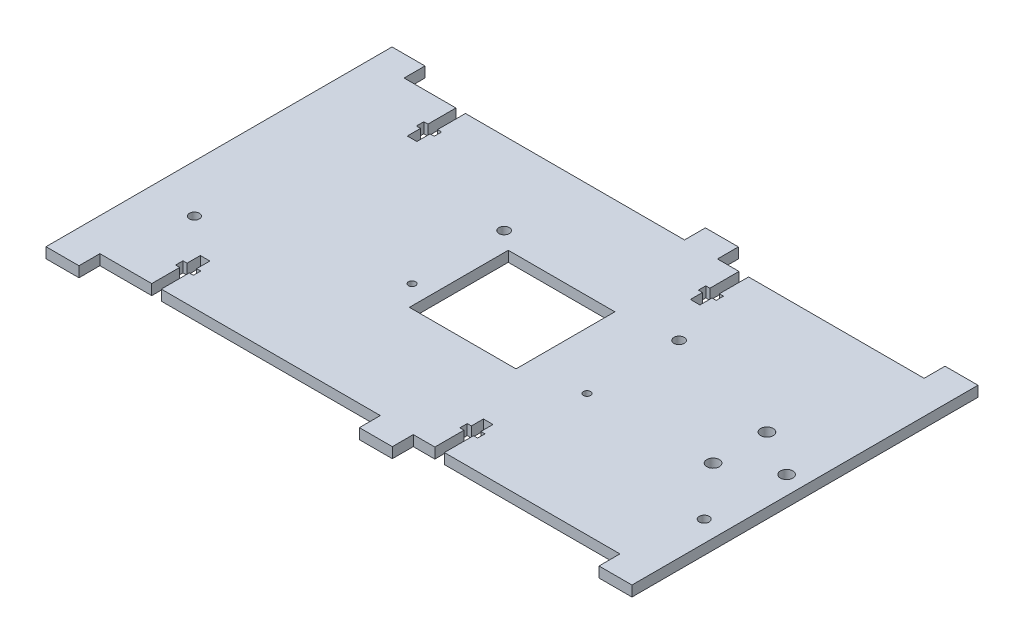
SolidWorks part; units mm, degrees
ref_plane "Front Plane" through (0, 0, 0) normal (0, 0, 1) x (1, 0, 0)
ref_plane "Top Plane" through (0, 0, 0) normal (0, 1, 0) x (1, 0, 0)
ref_plane "Right Plane" through (0, 0, 0) normal (1, 0, 0) x (0, 0, -1)
sketch "Sketch1" plane through (0, 0, 0) normal (0, 1, 0) x (1, 0, 0)
  line L0 (-67.1586, 70.4843) -> (-67.1586, 74.4928)
  line L1 (-92.8881, 91.5843) -> (-82.8881, 91.5843)
  line L2 (-92.8881, 91.5843) -> (-92.8881, -13.4157)
  line L3 (84.9141, 91.5843) -> (84.9141, -13.4157)
  line L5 (-64.2586, 85.2343) -> (2.2019, 85.2343)
  line L6 (-67.1586, 85.2343) -> (-67.1586, 76.7428)
  line L7 (-67.1586, 70.4843) -> (-64.2586, 70.4843)
  line L8 (-64.2586, 85.2343) -> (-64.2586, 76.7428)
  line L9 (-68.4086, 76.7428) -> (-67.1586, 76.7428)
  line L10 (-68.4086, 76.7428) -> (-68.4086, 74.4928)
  line L11 (-68.4086, 74.4928) -> (-67.1586, 74.4928)
  line L12 (-63.0086, 76.7428) -> (-63.0086, 74.4928)
  line L13 (18.7441, 70.4843) -> (18.7441, 74.1476)
  line L14 (-82.8881, 91.5843) -> (-82.8881, 85.2343)
  line L15 (-82.8881, 85.2343) -> (-67.1586, 85.2343)
  line L16 (2.2019, 91.5843) -> (2.2019, 85.2343)
  line L17 (-64.2586, 70.4843) -> (-64.2586, 74.4928)
  line L18 (-64.2586, 74.4928) -> (-63.0086, 74.4928)
  line L19 (-64.2586, 76.7428) -> (-63.0086, 76.7428)
  line L20 (2.2019, 91.5843) -> (12.2019, 91.5843)
  line L21 (21.6441, 85.2343) -> (74.9141, 85.2343)
  line L22 (18.7441, 85.2343) -> (18.7441, 76.3976)
  line L23 (18.7441, 70.4843) -> (21.6441, 70.4843)
  line L24 (21.6441, 85.2343) -> (21.6441, 76.3976)
  line L25 (17.4941, 76.3976) -> (18.7441, 76.3976)
  line L26 (17.4941, 76.3976) -> (17.4941, 74.1476)
  line L27 (17.4941, 74.1476) -> (18.7441, 74.1476)
  line L28 (22.8941, 76.3976) -> (22.8941, 74.1476)
  line L29 (12.2019, 91.5843) -> (12.2019, 85.2343)
  line L30 (12.2019, 85.2343) -> (18.7441, 85.2343)
  line L31 (74.9141, 91.5843) -> (74.9141, 85.2343)
  line L32 (21.6441, 70.4843) -> (21.6441, 74.1476)
  line L33 (21.6441, 74.1476) -> (22.8941, 74.1476)
  line L34 (21.6441, 76.3976) -> (22.8941, 76.3976)
  line L35 (74.9141, 91.5843) -> (84.9141, 91.5843)
  line L36 (-82.8881, -7.0657) -> (-67.1586, -7.0657)
  line L37 (74.9141, -13.4157) -> (84.9141, -13.4157)
  line L38 (21.6441, 1.771) -> (22.8941, 1.771)
  line L39 (21.6441, 4.021) -> (22.8941, 4.021)
  line L40 (21.6441, 7.6843) -> (21.6441, 4.021)
  line L41 (74.9141, -13.4157) -> (74.9141, -7.0657)
  line L42 (12.2019, -7.0657) -> (18.7441, -7.0657)
  line L43 (12.2019, -13.4157) -> (12.2019, -7.0657)
  line L44 (22.8941, 1.771) -> (22.8941, 4.021)
  line L45 (17.4941, 4.021) -> (18.7441, 4.021)
  line L46 (17.4941, 1.771) -> (17.4941, 4.021)
  line L47 (17.4941, 1.771) -> (18.7441, 1.771)
  line L48 (21.6441, -7.0657) -> (21.6441, 1.771)
  line L49 (18.7441, 7.6843) -> (21.6441, 7.6843)
  line L50 (18.7441, -7.0657) -> (18.7441, 1.771)
  line L51 (21.6441, -7.0657) -> (74.9141, -7.0657)
  line L52 (2.2019, -13.4157) -> (12.2019, -13.4157)
  line L53 (-64.2586, 1.4258) -> (-63.0086, 1.4258)
  line L54 (-64.2586, 3.6758) -> (-63.0086, 3.6758)
  line L55 (-64.2586, 7.6843) -> (-64.2586, 3.6758)
  line L56 (2.2019, -13.4157) -> (2.2019, -7.0657)
  line L57 (-82.8881, -13.4157) -> (-82.8881, -7.0657)
  line L58 (18.7441, 7.6843) -> (18.7441, 4.021)
  line L59 (-63.0086, 1.4258) -> (-63.0086, 3.6758)
  line L60 (-68.4086, 3.6758) -> (-67.1586, 3.6758)
  line L61 (-68.4086, 1.4258) -> (-68.4086, 3.6758)
  line L62 (-68.4086, 1.4258) -> (-67.1586, 1.4258)
  line L63 (-64.2586, -7.0657) -> (-64.2586, 1.4258)
  line L64 (-67.1586, 7.6843) -> (-64.2586, 7.6843)
  line L65 (-67.1586, -7.0657) -> (-67.1586, 1.4258)
  line L66 (-64.2586, -7.0657) -> (2.2019, -7.0657)
  line L67 (-92.8881, -13.4157) -> (-82.8881, -13.4157)
  line L68 (-67.1586, 7.6843) -> (-67.1586, 3.6758)
  line L69 (-21.8187, 55.7843) -> (10.5266, 55.7843)
  line L70 (-21.8187, 55.7843) -> (-21.8187, 25.7843)
  line L71 (-21.8187, 25.7843) -> (10.5266, 25.7843)
  line L72 (10.5266, 55.7843) -> (10.5266, 25.7843)
  circle A1 centre (79.3541, 39.0843) radius 1.9
  circle A2 centre (65.1941, 30.909) radius 1.9
  circle A3 centre (65.1941, 47.2596) radius 1.9
  circle A4 centre (27.7774, 58.0256) radius 1.5835
  circle A5 centre (78.5774, 14.8456) radius 1.5071
  circle A6 centre (27.7774, 30.0856) radius 1.0795
  circle A7 centre (-78.423, 17.1475) radius 1.5071
  circle A8 centre (-27.6231, 32.3875) radius 1.0795
  circle A9 centre (-27.6231, 60.3275) radius 1.5835
  point P76 (-21.8187, 40.7843)
  dimension "D1" = 1.25
  dimension "D2" = 2.9
  dimension "D3" = 1.25
  dimension "D4" = 2.25
  dimension "D5" = 14.75
  dimension "D6" = 1.25
  dimension "D7" = 1.25
  dimension "D8" = 2.25
  dimension "D9" = 14.75
  dimension "D10" = 10
  dimension "D11" = 10
  dimension "D12" = 10
  dimension "D13" = 6.35
  dimension "D14" = 6.35
  dimension "D15" = 53.27
  dimension "D16" = 105
  dimension "D17" = 95.09
  dimension "D18" = 30
  dimension "D19" = 105
  dimension "D23" = 50.8
  dimension "D24" = 6.35
extrude "Extrude1" add sketch "Sketch1" along normal blind 3.175
